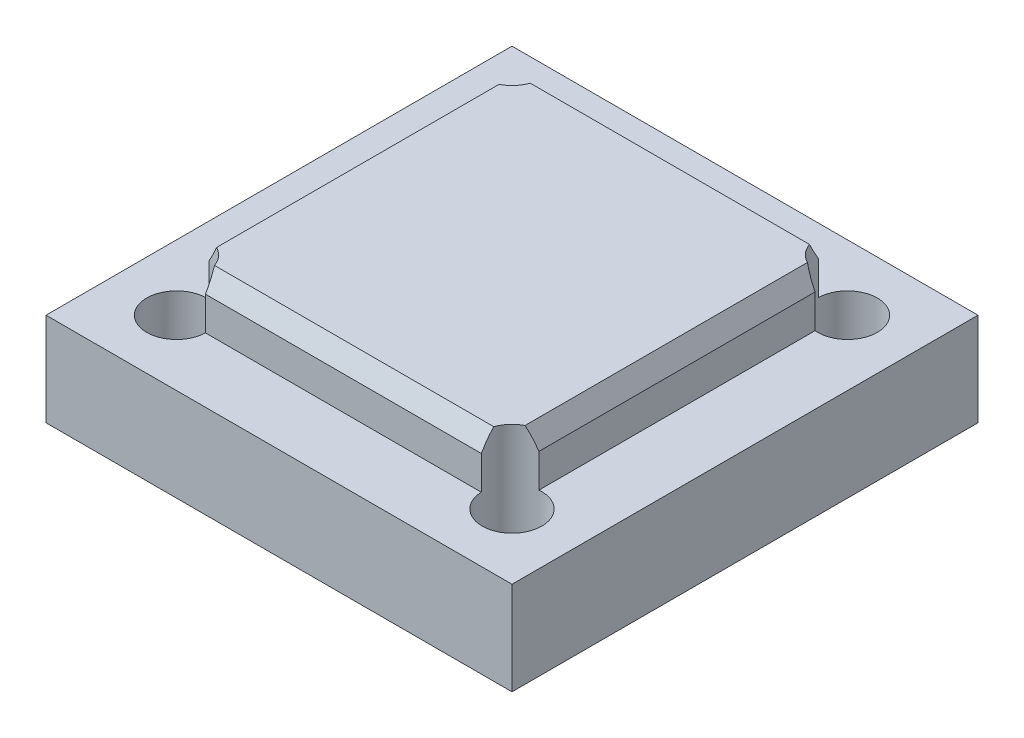
SolidWorks part; units mm, degrees
ref_plane "Спереди" through (0, 0, 0) normal (0, 0, 1) x (1, 0, 0)
ref_plane "Сверху" through (0, 0, 0) normal (0, 1, 0) x (1, 0, 0)
ref_plane "Справа" through (0, 0, 0) normal (1, 0, 0) x (0, 0, -1)
sketch "Sketch1" plane through (0, 0, 0) normal (0, 1, 0) x (1, 0, 0)
  line L1 (12.5, -12.5) -> (-12.5, -12.5)
  line L2 (12.5, -12.5) -> (12.5, 12.5)
  line L3 (12.5, 12.5) -> (-12.5, 12.5)
  line L4 (-12.5, -12.5) -> (-12.5, 12.5)
  line L5 (12.5, -12.5) -> (-12.5, 12.5) construction
  line L6 (12.5, 12.5) -> (-12.5, -12.5) construction
  point P0 (0, 0)
  dimension "D1" = 25
extrude "Boss-Extrude1" add sketch "Sketch1" along normal blind 5
sketch "Sketch4" plane through (0, 5, 0) normal (0, 1, 0) x (1, 0, 0)
  circle A0 centre (0, 0) radius 4.15
  dimension "D1" = 8.3
extrude "Cut-Extrude2" cut sketch "Sketch4" against normal through all
sketch "Sketch9" plane through (0, 5, 0) normal (0, 1, 0) x (1, 0, 0)
  line L1 (8.85, 9.0463) -> (-8.85, 9.0463)
  line L2 (8.85, 9.0463) -> (8.85, -9.0463)
  line L3 (8.85, -9.0463) -> (-8.85, -9.0463)
  line L4 (-8.85, 9.0463) -> (-8.85, -9.0463)
  line L5 (8.85, 9.0463) -> (-8.85, -9.0463) construction
  line L6 (8.85, -9.0463) -> (-8.85, 9.0463) construction
  line L7 (-3.7, -6.4086) -> (3.7, -6.4086) construction
  line L8 (3.7, -6.4086) -> (7.4, 0) construction
  line L9 (7.4, 0) -> (3.7, 6.4086) construction
  line L10 (3.7, 6.4086) -> (-3.7, 6.4086) construction
  line L11 (-3.7, 6.4086) -> (-7.4, 0) construction
  line L12 (-7.4, 0) -> (-3.7, -6.4086) construction
  circle A0 centre (0, 0) radius 7.4 construction
  point P0 (0, 0)
  dimension "D2" = 14.8
  dimension "D1" = 17.7
extrude "Boss-Extrude3" add sketch "Sketch9" along normal blind 2.8
sketch "Sketch6" plane through (0, 5, 0) normal (0, 1, 0) x (1, 0, 0)
  line L1 (-9, 9) -> (9, 9) construction
  line L2 (-9, 9) -> (-9, -9) construction
  line L3 (-9, -9) -> (9, -9) construction
  line L4 (9, 9) -> (9, -9) construction
  line L5 (-9, 9) -> (9, -9) construction
  line L6 (-9, -9) -> (9, 9) construction
  circle A0 centre (9, -9) radius 1.6
  circle A1 centre (-9, -9) radius 1.6
  circle A2 centre (-9, 9) radius 1.6
  circle A3 centre (9, 9) radius 1.6
  point P0 (0, 0)
  dimension "D1" = 3.2
  dimension "D2" = 18
extrude "Cut-Extrude4" cut sketch "Sketch6" against normal through all both and the other way through all
chamfer "Chamfer1" distance 1 angle 30 4 edges at (8.85, 7.8, 0) (0, 7.8, -9.0463) (-8.85, 7.8, 0) (0, 7.8, 9.0463)
sketch "Sketch10" plane through (0, 5, 0) normal (0, -1, 0) x (1, 0, 0)
  circle A0 centre (0, 0) radius 4.15
extrude "Boss-Extrude4" add sketch "Sketch10" along normal up to surface (5 mm away) up to face at (-9, 0, 10.6)
